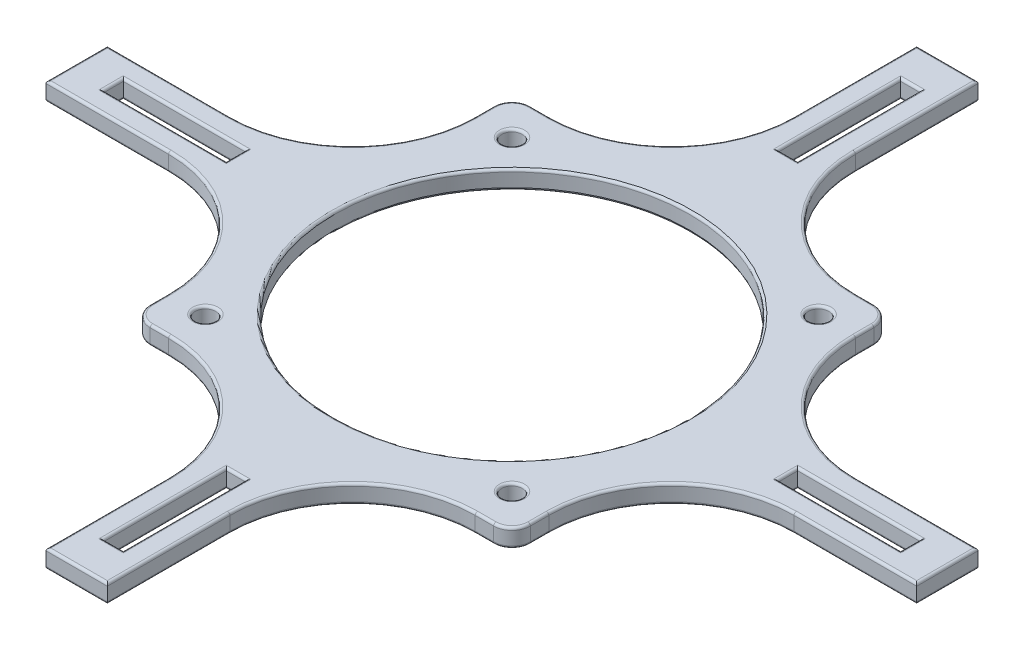
SolidWorks part; units mm, degrees
ref_plane "Front Plane" through (0, 0, 0) normal (0, 0, 1) x (1, 0, 0)
ref_plane "Top Plane" through (0, 0, 0) normal (0, 1, 0) x (1, 0, 0)
ref_plane "Right Plane" through (0, 0, 0) normal (1, 0, 0) x (0, 0, -1)
sketch "Sketch1" plane through (0, 0, 0) normal (0, 1, 0) x (1, 0, 0)
  line L1 (0, 0) -> (62, 0)
  line L2 (0, 0) -> (0, -62)
  line L3 (0, -62) -> (62, -62)
  line L4 (62, 0) -> (62, -62)
  dimension "D1" = 62
  dimension "D2" = 62
extrude "Boss-Extrude1" add sketch "Sketch1" along normal blind 3
sketch "Sketch2" plane through (0, 0, 0) normal (0, -1, 0) x (-1, 0, 0)
  circle A0 centre (-56, -56) radius 1.65
  circle A1 centre (-6, -56) radius 1.65
  circle A2 centre (-6, -6) radius 1.65
  circle A3 centre (-56, -6) radius 1.65
  circle A4 centre (-31, -31) radius 29
  dimension "D1" = 3.3
  dimension "D2" = 3.3
  dimension "D3" = 3.3
  dimension "D4" = 3.3
extrude "Cut-Extrude1" cut sketch "Sketch2" against normal blind 10
sketch "Sketch3" plane through (0, 3, 0) normal (0, 1, 0) x (1, 0, 0)
  line L0 (62, 0) -> (0, 0) construction
  line L1 (26, 0) -> (36, 0)
  line L2 (26, 0) -> (26, 40)
  line L3 (26, 40) -> (36, 40)
  line L4 (36, 0) -> (36, 40)
  line L5 (0, 0) -> (0, -62) construction
  line L6 (0, -26) -> (-40, -26)
  line L7 (0, -26) -> (0, -36)
  line L8 (0, -36) -> (-40, -36)
  line L9 (-40, -26) -> (-40, -36)
  line L20 (62, -62) -> (62, 0) construction
  line L21 (62, -26) -> (102, -26)
  line L22 (62, -26) -> (62, -36)
  line L23 (62, -36) -> (102, -36)
  line L24 (102, -26) -> (102, -36)
  line L25 (0, -62) -> (62, -62) construction
  line L26 (26, -62) -> (36, -62)
  line L27 (26, -62) -> (26, -102)
  line L28 (26, -102) -> (36, -102)
  line L29 (36, -62) -> (36, -102)
  point P24 (31, 0)
  point P25 (31, 0)
  point P26 (62, -31)
  point P27 (62, -31)
  point P28 (31, -62)
  point P29 (31, -62)
  point P30 (0, -31)
  point P31 (0, -31)
  dimension "D1" = 10
  dimension "D2" = 10
  dimension "D3" = 10
  dimension "D4" = 0
  dimension "D5" = 0
  dimension "D6" = 0
  dimension "D7" = 10
  dimension "D8" = 0
  dimension "D9" = 40
  dimension "D10" = 40
  dimension "D11" = 40
  dimension "D12" = 40
extrude "Boss-Extrude2" add sketch "Sketch3" against normal blind 3
sketch "Sketch4" plane through (0, 3, 0) normal (0, 1, 0) x (1, 0, 0)
  line L0 (102, -26) -> (62, -26) construction
  line L1 (76, -29.4) -> (96, -29.4)
  line L2 (76, -29.4) -> (76, -32.6)
  line L3 (76, -32.6) -> (96, -32.6)
  line L4 (96, -29.4) -> (96, -32.6)
  line L5 (102, -36) -> (102, -26) construction
  line L18 (29.4, 14) -> (32.6, 14)
  line L19 (29.4, 14) -> (29.4, 34)
  line L20 (29.4, 34) -> (32.6, 34)
  line L21 (32.6, 14) -> (32.6, 34)
  line L22 (-14, -32.6) -> (-14, -29.4)
  line L23 (-14, -32.6) -> (-34, -32.6)
  line L24 (-34, -32.6) -> (-34, -29.4)
  line L25 (-14, -29.4) -> (-34, -29.4)
  line L26 (32.6, -76) -> (29.4, -76)
  line L27 (32.6, -76) -> (32.6, -96)
  line L28 (32.6, -96) -> (29.4, -96)
  line L29 (29.4, -76) -> (29.4, -96)
  point P23 (31, -31)
  dimension "D1" = 3.2
  dimension "D2" = 3.4
  dimension "D3" = 6
  dimension "D4" = 20
  dimension "D5" = 4
extrude "Cut-Extrude2" cut sketch "Sketch4" against normal blind 10
fillet "Fillet1" radius 20 8 edges at (36, 1.5, 0) (26, 1.5, 0) (0, 1.5, 26) (0, 1.5, 36) (26, 1.5, 62) (36, 1.5, 62) (62, 1.5, 26) (62, 1.5, 36)
fillet "Fillet4" radius 3 4 edges at (62, 1.5, 0) (62, 1.5, 62) (0, 1.5, 62) (0, 1.5, 0)
fillet "Fillet5" radius 0.4 53 edges at (67.8579, 3, 20.1421) (92, 3, 26) (92, 3, 36) (67.8579, 3, 41.8579) (62, 3, 57.5) (61.1213, 3, 61.1213) (57.5, 3, 62) (41.8579, 3, 67.8579) (36, 3, 92) (26, 3, 92) (20.1421, 3, 67.8579) (4.5, 3, 62) (0.8787, 3, 61.1213) (0, 3, 57.5) (-5.8579, 3, 41.8579) (-30, 3, 36) (-30, 3, 26) (-5.8579, 3, 20.1421) (0, 3, 4.5) (0.8787, 3, 0.8787) (4.5, 3, 0) (20.1421, 3, -5.8579) (26, 3, -30) (36, 3, -30) (41.8579, 3, -5.8579) (57.5, 3, 0) (61.1213, 3, 0.8787) (62, 3, 4.5) (56, 3, 57.65) (56, 3, 7.65) (31, 3, 60) (6, 3, 7.65) (6, 3, 57.65) (102, 3, 31) (31, 3, 102) (-40, 3, 31) (31, 3, -40) (86, 3, 32.6) (96, 3, 31) (86, 3, 29.4) (76, 3, 31) (31, 3, 76) (29.4, 3, 86) (31, 3, 96) (32.6, 3, 86) (-14, 3, 31) (-24, 3, 29.4) (-34, 3, 31) (-24, 3, 32.6) (31, 3, -14) (32.6, 3, -24) (31, 3, -34) (29.4, 3, -24)
fillet "Fillet7" radius 0.4 53 edges at (41.8579, 0, -5.8579) (36, 0, -30) (26, 0, -30) (20.1421, 0, -5.8579) (4.5, 0, 0) (0.8787, 0, 0.8787) (0, 0, 4.5) (-5.8579, 0, 20.1421) (-30, 0, 26) (-30, 0, 36) (-5.8579, 0, 41.8579) (0, 0, 57.5) (0.8787, 0, 61.1213) (4.5, 0, 62) (20.1421, 0, 67.8579) (26, 0, 92) (36, 0, 92) (41.8579, 0, 67.8579) (57.5, 0, 62) (61.1213, 0, 61.1213) (62, 0, 57.5) (67.8579, 0, 41.8579) (92, 0, 36) (92, 0, 26) (67.8579, 0, 20.1421) (62, 0, 4.5) (61.1213, 0, 0.8787) (57.5, 0, 0) (56, 0, 54.35) (56, 0, 4.35) (31, 0, 2) (6, 0, 4.35) (6, 0, 54.35) (31, 0, -40) (-40, 0, 31) (31, 0, 102) (102, 0, 31) (96, 0, 31) (86, 0, 32.6) (76, 0, 31) (86, 0, 29.4) (29.4, 0, 86) (31, 0, 76) (32.6, 0, 86) (31, 0, 96) (-24, 0, 29.4) (-14, 0, 31) (-24, 0, 32.6) (-34, 0, 31) (32.6, 0, -24) (31, 0, -14) (29.4, 0, -24) (31, 0, -34)
